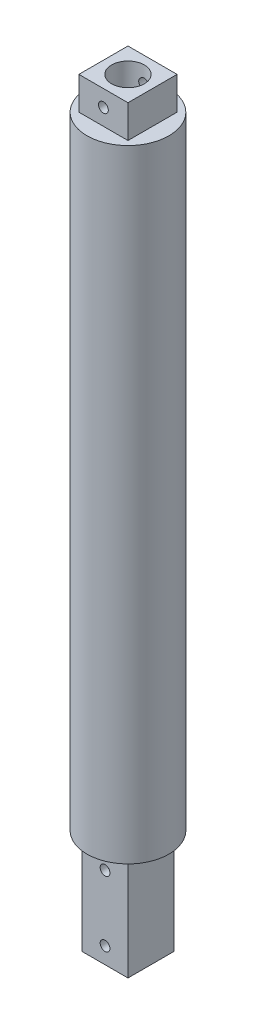
SolidWorks part; units mm, degrees
material "1060 Alloy"
ref_plane "Front Plane" through (0, 0, 0) normal (0, 0, 1) x (1, 0, 0)
ref_plane "Top Plane" through (0, 0, 0) normal (0, 1, 0) x (1, 0, 0)
ref_plane "Right Plane" through (0, 0, 0) normal (1, 0, 0) x (0, 0, -1)
sketch "Sketch1" plane through (0, 0, 0) normal (0, 0, 1) x (1, 0, 0)
  line L0 (0, 0) -> (0, -14105.0389) construction
  line L1 (-7, 32) -> (7, 32)
  line L2 (-7, 32) -> (-7, 0)
  line L3 (-7, 0) -> (7, 0)
  line L4 (7, 32) -> (7, 0)
  circle A0 centre (0, 5) radius 1.5
  circle A1 centre (0, 25) radius 1.5
  point P5 (0, 0)
  dimension "D4" = 3
  dimension "D5" = 3
  dimension "D1" = 14
  dimension "D2" = 32
  dimension "D3" = 20
  dimension "D6" = 5
extrude "Boss-Extrude1" add sketch "Sketch1" along normal mid plane 14
sketch "Sketch3" plane through (0, 32, 0) normal (0, 1, 0) x (1, 0, 0)
  circle A0 centre (0, 0) radius 12.5
  dimension "D1" = 25
extrude "Boss-Extrude2" add sketch "Sketch3" along normal blind 200
sketch "Sketch4" plane through (0, 232, 0) normal (0, 1, 0) x (1, 0, 0)
  line L1 (-7.5, 7.5) -> (7.5, 7.5)
  line L2 (-7.5, 7.5) -> (-7.5, -7.5)
  line L3 (-7.5, -7.5) -> (7.5, -7.5)
  line L4 (7.5, 7.5) -> (7.5, -7.5)
  line L5 (-7.5, 7.5) -> (7.5, -7.5) construction
  line L6 (-7.5, -7.5) -> (7.5, 7.5) construction
  point P0 (0, 0)
  dimension "D1" = 15
  dimension "D2" = 15
extrude "Cut-Extrude1" cut sketch "Sketch4" against normal blind 10 flip side to cut
sketch "Sketch5" plane through (0, 0, 7.5) normal (0, 0, 1) x (1, 0, 0)
  line L0 (-7.5, 227) -> (7.5, 227) construction
  line L1 (-7.5, 222) -> (-7.5, 232) construction
  line L2 (7.5, 222) -> (7.5, 232) construction
  line L3 (0, 232) -> (0, 222) construction
  line L4 (-7.5, 232) -> (7.5, 232) construction
  line L5 (12.5, 222) -> (-12.5, 222) construction
  circle A0 centre (0, 227) radius 1.5
  dimension "D1" = 3
extrude "Cut-Extrude2" cut sketch "Sketch5" against normal through all
sketch "Sketch6" plane through (0, 0, 0) normal (0, -1, 0) x (1, 0, 0)
  circle A0 centre (0, 0) radius 5
  dimension "D1" = 10
extrude "Cut-Extrude3" cut sketch "Sketch6" against normal through all
